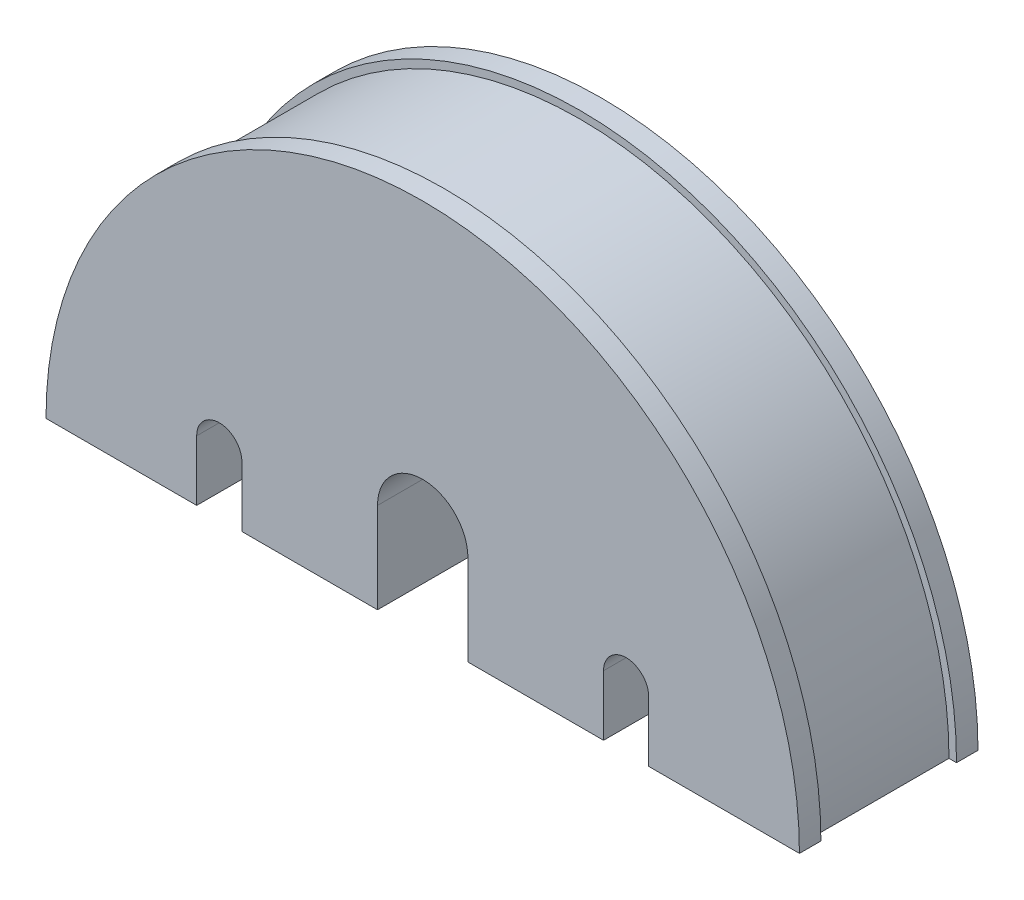
SolidWorks part; units mm, degrees
ref_plane "前视基准面" through (0, 0, 0) normal (0, 0, 1) x (1, 0, 0)
ref_plane "上视基准面" through (0, 0, 0) normal (0, 1, 0) x (1, 0, 0)
ref_plane "右视基准面" through (0, 0, 0) normal (1, 0, 0) x (0, 0, -1)
other "Configuration Table"
sketch "草图1" plane through (0, 0, 0) normal (0, 0, 1) x (1, 0, 0)
  line L0 (-500, 0) -> (-300, 0)
  line L1 (0, 56.4108) -> (0, -32.2973) construction
  line L2 (-60, 120) -> (-60, 0)
  line L3 (60, 120) -> (60, 0)
  line L4 (60, 0) -> (240, 0)
  line L5 (-300, 80) -> (-300, 0)
  line L6 (-240, 80) -> (-240, 0)
  line L7 (240, 80) -> (240, 0)
  line L8 (300, 80) -> (300, 0)
  line L9 (300, 0) -> (500, 0)
  line L10 (-240, 0) -> (-60, 0)
  arc A0 (500, 0) -> (-500, 0) centre (0, 0) ccw
  arc A1 (60, 120) -> (-60, 120) centre (0, 120) ccw
  arc A2 (-240, 80) -> (-300, 80) centre (-270, 80) ccw
  arc A3 (240, 80) -> (300, 80) centre (270, 80) cw
  dimension "D1" = 1000
  dimension "D2" = 120
  dimension "D4" = 60
  dimension "D5" = 270
  dimension "D3" = 120
  dimension "D6" = 80
extrude "凸台-拉伸1" add sketch "草图1" along normal mid plane 237
sketch "草图2" plane through (0, 0, 0) normal (0, 1, 0) x (1, 0, 0)
  line L0 (0, 0) -> (698.9361, 0) construction
  line L1 (500, -118.5) -> (500, 118.5) construction
  line L2 (490, 90) -> (510, 90)
  line L3 (490, 90) -> (490, -90)
  line L4 (490, -90) -> (510, -90)
  line L5 (510, 90) -> (510, -90)
  line L6 (490, 90) -> (510, -90) construction
  line L7 (490, -90) -> (510, 90) construction
  line L8 (0, 254.4016) -> (0, -339.6199) construction
  point P3 (500, 0)
  dimension "D1" = 180
  dimension "D2" = 10
revolve "切除-旋转1" cut sketch "草图2" angle 180 about L8
